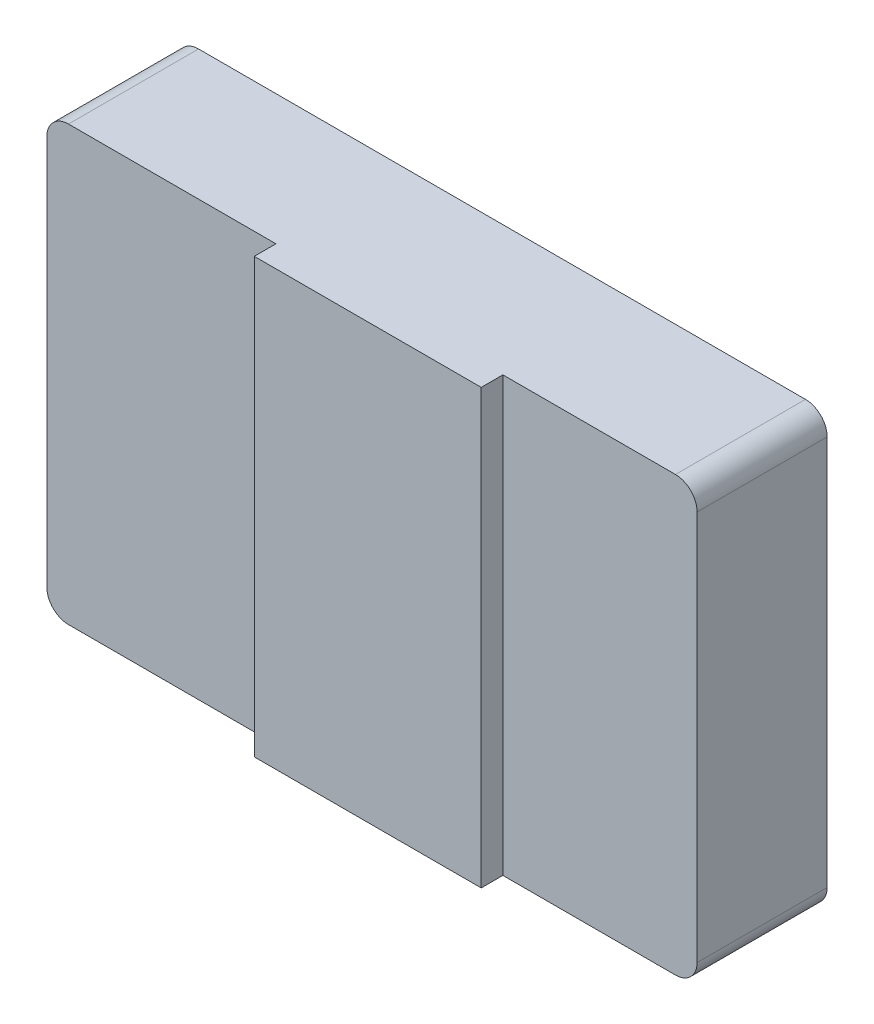
SolidWorks part; units mm, degrees
material "硅"
ref_plane "前视基准面" through (0, 0, 0) normal (0, 0, 1) x (1, 0, 0)
ref_plane "上视基准面" through (0, 0, 0) normal (0, 1, 0) x (1, 0, 0)
ref_plane "右视基准面" through (0, 0, 0) normal (1, 0, 0) x (0, 0, -1)
sketch "草图1" plane through (0, 0, 0) normal (0, 0, 1) x (1, 0, 0)
  line L1 (0, 0) -> (3, 0)
  line L2 (0, 0) -> (0, 2)
  line L3 (0, 2) -> (3, 2)
  line L4 (3, 0) -> (3, 2)
  dimension "D1" = 3
  dimension "D2" = 2
extrude "凸台-拉伸1" add sketch "草图1" along normal blind 0.7
sketch "草图2" plane through (0, 0, 0.7) normal (0, 0, 1) x (1, 0, 0)
  line L0 (3, 2) -> (0, 2) construction
  line L1 (1.057, 2) -> (2.104, 2)
  line L2 (1.057, 2) -> (1.057, 0)
  line L3 (1.057, 0) -> (2.104, 0)
  line L4 (2.104, 2) -> (2.104, 0)
  line L5 (0, 0) -> (3, 0) construction
extrude "切除-拉伸1" cut sketch "草图2" against normal blind 0.1 flip side to cut
fillet "圆角1" radius 0.1 4 edges at (3, 2, 0.3) (3, 0, 0.3) (0, 0, 0.3) (0, 2, 0.3)
